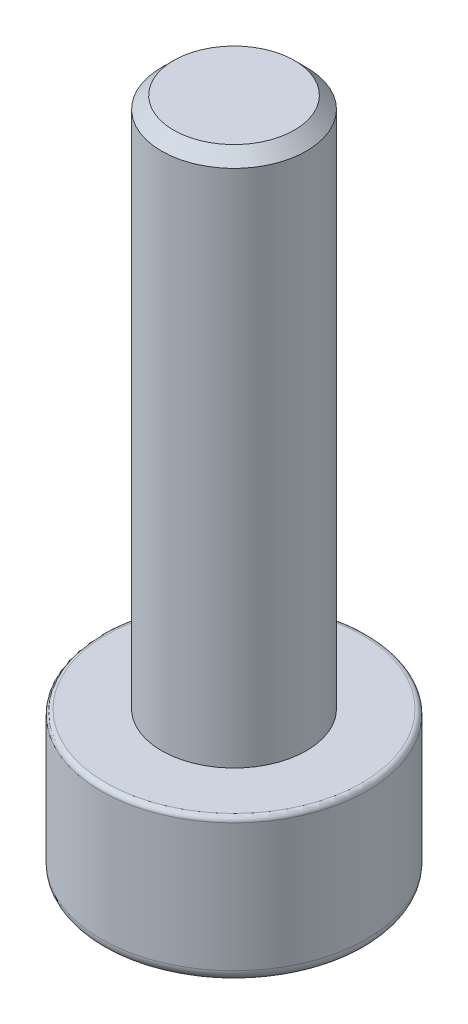
SolidWorks part; units mm, degrees
ref_plane "Front Plane" through (0, 0, 0) normal (0, 0, 1) x (1, 0, 0)
ref_plane "Top Plane" through (0, 0, 0) normal (0, 1, 0) x (1, 0, 0)
ref_plane "Right Plane" through (0, 0, 0) normal (1, 0, 0) x (0, 0, -1)
sketch "Sketch1" plane through (0, 0, 0) normal (0, 1, 0) x (1, 0, 0)
  circle A0 centre (0, 0) radius 2.75
  dimension "D1" = 5.5
extrude "Boss-Extrude1" add sketch "Sketch1" along normal blind 3
sketch "Sketch2" plane through (0, 3, 0) normal (0, 1, 0) x (1, 0, 0)
  circle A0 centre (0, 0) radius 1.5
  dimension "D1" = 3
extrude "Boss-Extrude2" add sketch "Sketch2" along normal blind 11 contours A0
sketch "Sketch3" plane through (0, 0, 0) normal (0, -1, 0) x (1, 0, 0)
  line L1 (0.9342, 0.9746) -> (-0.3769, 1.2963)
  line L2 (-0.3769, 1.2963) -> (-1.3111, 0.3217)
  line L3 (-1.3111, 0.3217) -> (-0.9342, -0.9746)
  line L4 (-0.9342, -0.9746) -> (0.3769, -1.2963)
  line L5 (0.3769, -1.2963) -> (1.3111, -0.3217)
  line L6 (1.3111, -0.3217) -> (0.9342, 0.9746)
  circle A0 centre (0, 0) radius 1.1691 construction
  dimension "D1" = 2.7
extrude "Cut-Extrude1" cut sketch "Sketch3" against normal blind 1.5
chamfer "Chamfer1" distance 0.25 distance2 0.25 6 edges at (-0.2786, 0, -1.1355) (-1.1226, 0, -0.3264) (-0.844, 0, 0.809) (0.2786, 0, 1.1355) (1.1226, 0, 0.3264) (0.844, 0, -0.809)
fillet "Fillet1" radius 0.25 1 edges at (0, 0, 2.75)
chamfer "Chamfer2" distance 0.25 angle 45 1 edges at (0, 14, 1.5)
fillet "Fillet2" radius 0.1 1 edges at (0, 3, 2.75)
